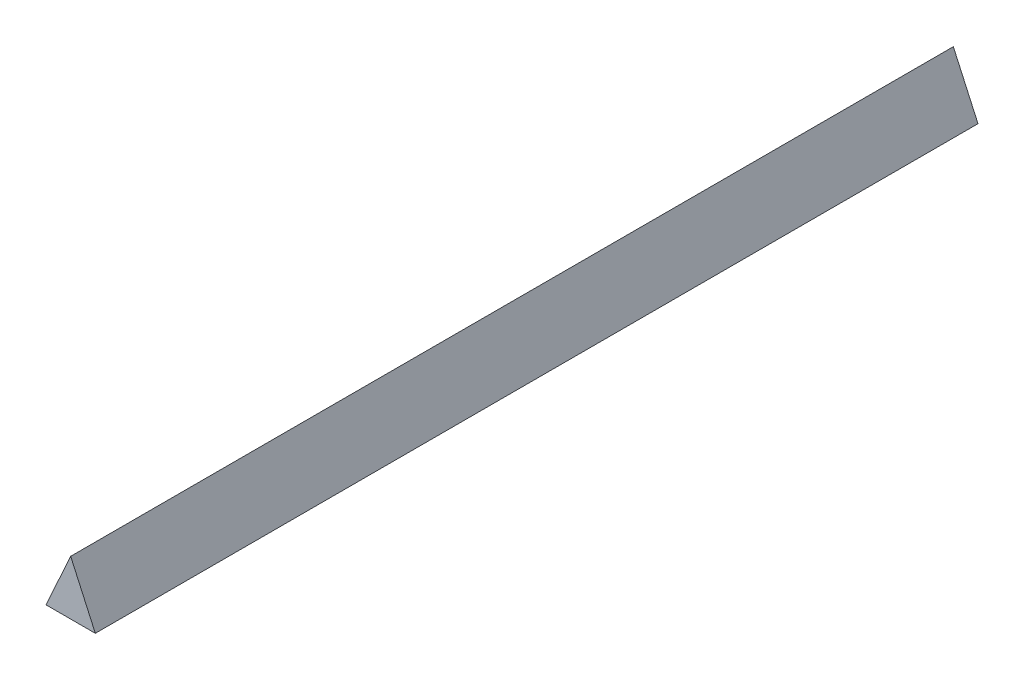
SolidWorks part; units mm, degrees
ref_plane "Спереди" through (0, 0, 0) normal (0, 0, 1) x (1, 0, 0)
ref_plane "Сверху" through (0, 0, 0) normal (0, 1, 0) x (1, 0, 0)
ref_plane "Справа" through (0, 0, 0) normal (1, 0, 0) x (0, 0, -1)
sketch "Эскиз1" plane through (0, 0, 0) normal (0, 0, 1) x (1, 0, 0)
  line L3 (-0.95, 0) -> (0.95, 0)
  line L4 (0.95, 0) -> (0, 2.0946)
  line L5 (0, 2.0946) -> (-0.95, 0)
  point P3 (-0.1164, 0)
  dimension "D1" = 1.9
  dimension "D2" = 2.3
extrude "Бобышка-Вытянуть1" add sketch "Эскиз1" along normal blind 34
